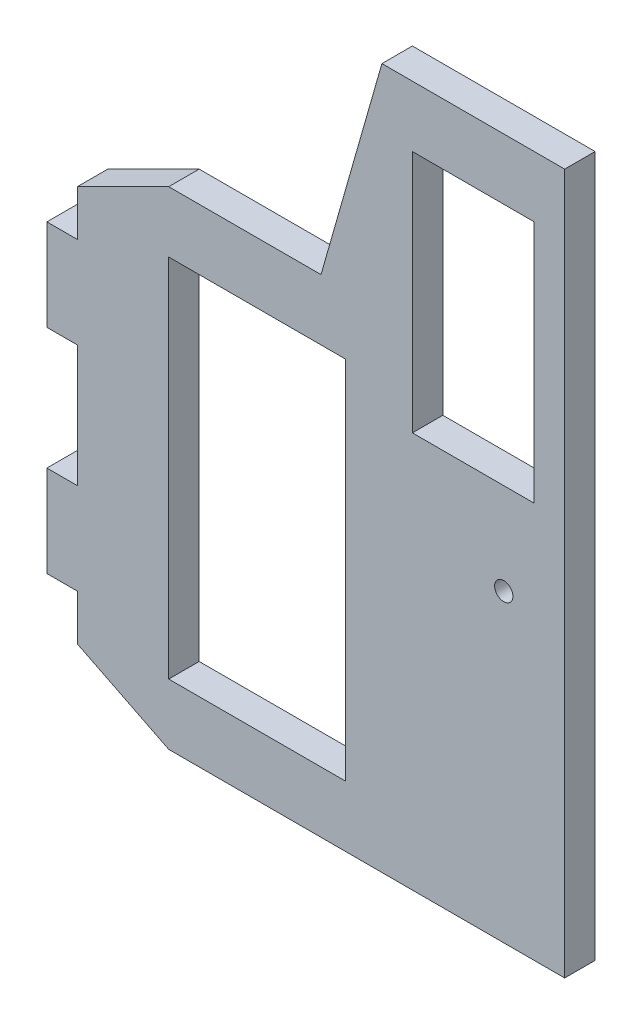
SolidWorks part; units mm, degrees
material "PVC Rigid"
ref_plane "Front Plane" through (0, 0, 0) normal (0, 0, 1) x (1, 0, 0)
ref_plane "Top Plane" through (0, 0, 0) normal (0, 1, 0) x (1, 0, 0)
ref_plane "Right Plane" through (0, 0, 0) normal (1, 0, 0) x (0, 0, -1)
sketch "Sketch1" plane through (0, 0, 0) normal (0, 0, 1) x (1, 0, 0)
  line L0 (0, 31.7838) -> (10, 66.7838)
  line L1 (-40, 31.7838) -> (0, 31.7838)
  line L2 (-40, 31.7838) -> (-40, -48.2162)
  line L3 (-40, -48.2162) -> (40, -48.2162)
  line L4 (40, 21.7838) -> (40, -48.2162)
  line L6 (40, 21.7838) -> (40, 66.7838)
  line L7 (40, 66.7838) -> (10, 66.7838)
  point P4 (0, 0)
  dimension "D1" = 80
  dimension "D2" = 80
  dimension "D3" = 45
  dimension "D4" = 30
  dimension "D5" = 70
extrude "Boss-Extrude1" add sketch "Sketch1" along normal blind 5
sketch "Sketch2" plane through (0, 0, 5) normal (0, 0, 1) x (1, 0, 0)
  line L0 (-40, 31.7838) -> (-40, -48.2162) construction
  line L1 (-25, 21.7838) -> (4, 21.7838)
  line L2 (-25, 21.7838) -> (-25, -38.2162)
  line L3 (-25, -38.2162) -> (4, -38.2162)
  line L4 (4, 21.7838) -> (4, -38.2162)
  line L5 (15, 56.7838) -> (35, 56.7838)
  line L6 (15, 56.7838) -> (15, 16.7838)
  line L7 (15, 16.7838) -> (35, 16.7838)
  line L8 (35, 56.7838) -> (35, 16.7838)
  line L9 (40, -48.2162) -> (40, 66.7838) construction
  line L10 (-40, -48.2162) -> (40, -48.2162) construction
  line L12 (40, 66.7838) -> (10, 66.7838) construction
  dimension "D1" = 29
  dimension "D2" = 20
  dimension "D3" = 60
  dimension "D4" = 40
  dimension "D5" = 15
  dimension "D6" = 5
  dimension "D7" = 10
  dimension "D8" = 10
extrude "Cut-Extrude1" cut sketch "Sketch2" against normal blind 5
sketch "Sketch3" plane through (-40, 0, 0) normal (-1, 0, 0) x (0, 0, 1)
  line L0 (0, 31.7838) -> (0, -48.2162) construction
  line L1 (0, 16.7838) -> (5, 16.7838)
  line L2 (0, 16.7838) -> (0, 1.7838)
  line L3 (0, 1.7838) -> (5, 1.7838)
  line L4 (5, 16.7838) -> (5, 1.7838)
  line L5 (5, 31.7838) -> (5, -48.2162) construction
  line L6 (5, -48.2162) -> (0, -48.2162) construction
  line L7 (0, -18.2162) -> (5, -18.2162)
  line L8 (0, -18.2162) -> (0, -33.2162)
  line L9 (0, -33.2162) -> (5, -33.2162)
  line L10 (5, -18.2162) -> (5, -33.2162)
  dimension "D1" = 15
  dimension "D2" = 15
  dimension "D3" = 20
  dimension "D4" = 15
extrude "Boss-Extrude2" add sketch "Sketch3" along normal blind 5
sketch "Sketch4" plane through (0, 0, 5) normal (0, 0, 1) x (1, 0, 0)
  line L0 (-40, 31.7838) -> (-25, 31.7838)
  line L1 (0, 31.7838) -> (-40, 31.7838) construction
  line L2 (-25, 31.7838) -> (-40, 24.2838)
  line L3 (-40, 31.7838) -> (-40, 16.7838) construction
  line L4 (-40, 24.2838) -> (-40, 31.7838)
  line L5 (-40, -48.2162) -> (-40, -40.7162)
  line L6 (-40, -33.2162) -> (-40, -48.2162) construction
  line L7 (-40, -40.7162) -> (-25, -48.2162)
  line L8 (-40, -48.2162) -> (40, -48.2162) construction
  line L9 (-25, -48.2162) -> (-40, -48.2162)
  dimension "D1" = 15
  dimension "D2" = 15
extrude "Cut-Extrude2" cut sketch "Sketch4" against normal blind 5
sketch "Sketch5" plane through (0, 0, 5) normal (0, 0, 1) x (1, 0, 0)
  line L0 (40, -48.2162) -> (40, 66.7838) construction
  line L1 (-25, -48.2162) -> (40, -48.2162) construction
  circle A0 centre (30, 1.7838) radius 1.5
  dimension "D1" = 3
  dimension "D2" = 10
  dimension "D3" = 50
extrude "Cut-Extrude3" cut sketch "Sketch5" against normal blind 5
